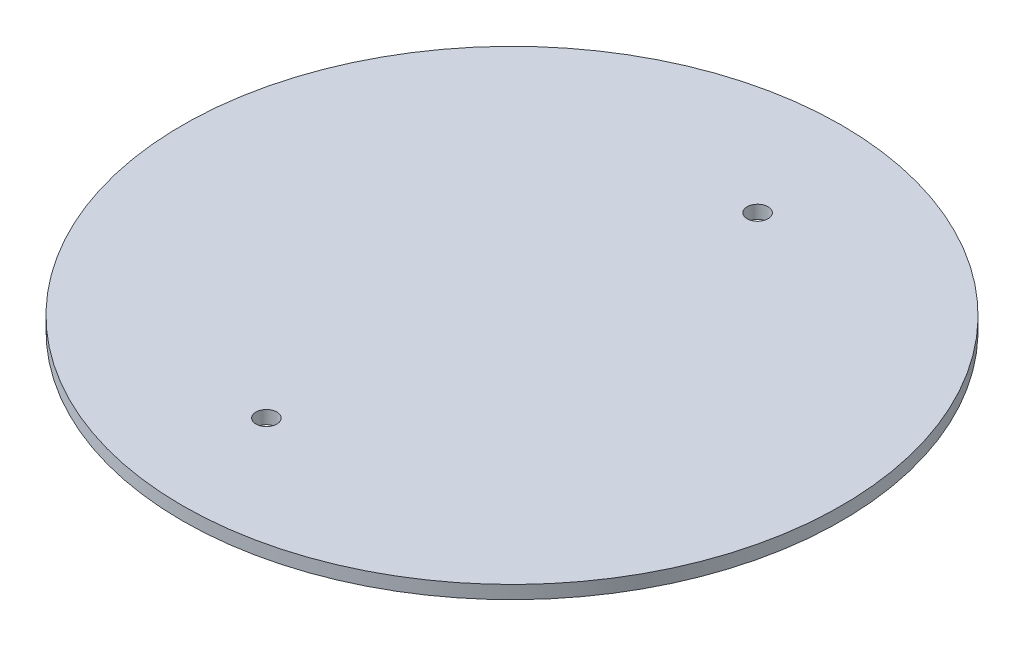
SolidWorks part; units mm, degrees
material "A-Glass Fiber"
ref_plane "Front Plane" through (0, 0, 0) normal (0, 0, 1) x (1, 0, 0)
ref_plane "Top Plane" through (0, 0, 0) normal (0, 1, 0) x (1, 0, 0)
ref_plane "Right Plane" through (0, 0, 0) normal (1, 0, 0) x (0, 0, -1)
sketch "Sketch1" plane through (0, 0, 0) normal (0, 1, 0) x (1, 0, 0)
  circle A0 centre (0, 0) radius 20
  circle A1 centre (2.058, 12.8467) radius 0.635
  circle A2 centre (-2.058, -12.8467) radius 0.635
  dimension "D1" = 40
  dimension "D5" = 12.8467
  dimension "D6" = 12.8467
  dimension "D7" = 2.058
  dimension "D2" = 1.27
  dimension "D3" = 1.27
  dimension "D4" = 2.058
extrude "PCB" add sketch "Sketch1" along normal blind 0.8
sketch "Sketch2" plane through (0, 0.8, 0) normal (0, 1, 0) x (1, 0, 0)
  line L0 (0, 0) -> (0, 20) construction
  circle A0 centre (0, 0) radius 20 construction
  point P7 (0, 0)
